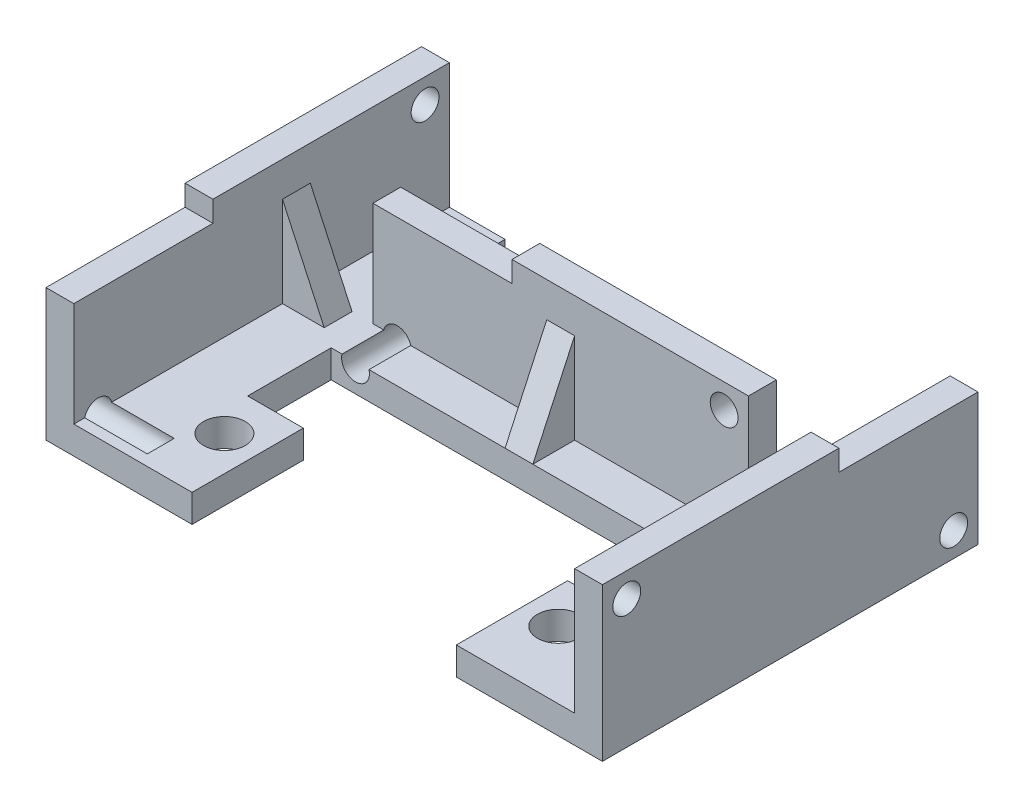
SolidWorks part; units mm, degrees
ref_plane "Front Plane" through (0, 0, 0) normal (0, 0, 1) x (1, 0, 0)
ref_plane "Top Plane" through (0, 0, 0) normal (0, 1, 0) x (1, 0, 0)
ref_plane "Right Plane" through (0, 0, 0) normal (1, 0, 0) x (0, 0, -1)
sketch "Sketch1" plane through (0, 0, 0) normal (0, 1, 0) x (1, 0, 0)
  line L0 (-13.5, 0) -> (13.5, 0)
  line L1 (13.5, 0) -> (13.5, 8)
  line L2 (13.5, 8) -> (20, 8)
  line L3 (20, 8) -> (20, -19)
  line L4 (20, -19) -> (13.5, -19)
  line L5 (13.5, -19) -> (13.5, -5)
  line L6 (13.5, -5) -> (-13.5, -5)
  line L7 (0, 0) -> (0, -5) construction
  line L8 (-13.5, -19) -> (-13.5, -5)
  line L9 (-20, -19) -> (-13.5, -19)
  line L10 (-20, 8) -> (-20, -19)
  line L11 (-13.5, 8) -> (-20, 8)
  line L12 (-13.5, 0) -> (-13.5, 8)
  dimension "D1" = 6.5
  dimension "D2" = 13.5
  dimension "D3" = 8
  dimension "D4" = 27
  dimension "D5" = 5
extrude "Boss-Extrude1" add sketch "Sketch1" along normal blind 11
sketch "Sketch2" plane through (0, 11, 0) normal (0, 1, 0) x (1, 0, 0)
  line L0 (-18, 8) -> (-18, -19)
  line L1 (-13.5, 8) -> (-20, 8) construction
  line L2 (-20, -19) -> (-13.5, -19) construction
  line L3 (-18, -19) -> (-13.5, -19)
  line L4 (-13.5, -19) -> (-13.5, -5)
  line L5 (-13.5, -5) -> (13.5, -5)
  line L6 (13.5, -5) -> (13.5, -19)
  line L7 (13.5, -19) -> (18, -19)
  line L8 (13.5, -19) -> (20, -19) construction
  line L9 (18, -19) -> (18, 8)
  line L10 (20, 8) -> (13.5, 8) construction
  line L11 (18, 8) -> (13.5, 8)
  line L12 (13.5, 8) -> (13.5, -2)
  line L13 (13.5, -2) -> (-13.5, -2)
  line L14 (-13.5, -2) -> (-13.5, 8)
  line L15 (-13.5, 8) -> (-18, 8)
  line L16 (-20, 8) -> (-20, -19) construction
  line L17 (20, -19) -> (20, 8) construction
  line L18 (13.5, 0) -> (-13.5, 0) construction
  dimension "D1" = 2
  dimension "D2" = 2
  dimension "D3" = 2
  dimension "D4" = 6.5
extrude "Cut-Extrude1" cut sketch "Sketch2" against normal blind 9
sketch "Sketch3" plane through (0, 0, 2) normal (0, 0, 1) x (1, 0, 0)
  line L0 (-13.5, 11) -> (-13.5, 9.5)
  line L1 (-13.5, 2) -> (-13.5, 11) construction
  line L2 (-13.5, 9.5) -> (-3.5, 9.5)
  line L3 (-3.5, 9.5) -> (-3.5, 11)
  line L4 (13.5, 11) -> (-13.5, 11) construction
  line L5 (-3.5, 11) -> (-13.5, 11)
  dimension "D1" = 1.5
  dimension "D2" = 10
extrude "Cut-Extrude2" cut sketch "Sketch3" against normal blind 9
sketch "Sketch4" plane through (18, 0, 0) normal (-1, 0, 0) x (0, 0, 1)
  line L0 (-8, 11) -> (-8, 9.5)
  line L1 (-8, 11) -> (-8, 0) construction
  line L2 (-8, 9.5) -> (2, 9.5)
  line L3 (2, 9.5) -> (2, 11)
  line L4 (-8, 11) -> (19, 11) construction
  line L5 (2, 11) -> (-8, 11)
  dimension "D1" = 10
  dimension "D2" = 1.5
extrude "Cut-Extrude3" cut sketch "Sketch4" against normal blind 9
sketch "Sketch5" plane through (-18, 0, 0) normal (1, 0, 0) x (0, 0, -1)
  line L0 (-19, 11) -> (-19, 9.5)
  line L1 (-19, 2) -> (-19, 11) construction
  line L2 (-19, 9.5) -> (-9, 9.5)
  line L3 (-9, 9.5) -> (-9, 11)
  line L4 (8, 11) -> (-19, 11) construction
  line L5 (-9, 11) -> (-19, 11)
  dimension "D1" = 10
  dimension "D2" = 1.5
extrude "Cut-Extrude4" cut sketch "Sketch5" against normal blind 9
sketch "Sketch6" plane through (0, 0, 0) normal (0, 0, -1) x (-1, 0, 0)
  circle A0 centre (11.75, 1.75) radius 1
  circle A1 centre (-11.75, 9.25) radius 1
extrude "Cut-Extrude5" cut sketch "Sketch6" against normal blind 9
sketch "Sketch7" plane through (20, 0, 0) normal (1, 0, 0) x (0, 0, -1)
  circle A0 centre (6.25, 1.75) radius 1
  circle A1 centre (-17.25, 9.25) radius 1
extrude "Cut-Extrude6" cut sketch "Sketch7" against normal blind 9
sketch "Sketch8" plane through (-20, 0, 0) normal (-1, 0, 0) x (0, 0, 1)
  circle A0 centre (17.25, 1.75) radius 1
  circle A1 centre (-6.25, 9.25) radius 1
extrude "Cut-Extrude10" cut sketch "Sketch8" against normal blind 9
sketch "Sketch10" plane through (0, 0, 0) normal (1, 0, 0) x (0, 0, -1)
  line L0 (-5, 2) -> (-2, 2)
  line L1 (-2, 2) -> (-2, 11) construction
  line L2 (-2, 2) -> (-2, 8.5)
  line L3 (-2, 8.5) -> (-5, 2)
  dimension "D1" = 3
  dimension "D2" = 6.5
extrude "Boss-Extrude2" add sketch "Sketch10" along normal mid plane 2
sketch "Sketch11" plane through (0, 2, 0) normal (0, 1, 0) x (1, 0, 0)
  line L0 (0, 8.5762) -> (0, 0) construction
  line L1 (-13.5, 8) -> (-14, 8)
  line L2 (-13.5, 8) -> (-18, 8) construction
  line L3 (-14, 8) -> (-14, 0)
  line L4 (-14, 0) -> (-13.5, 0)
  line L5 (-13.5, 0) -> (-13.5, 8)
  line L6 (13.5, 0) -> (13.5, 8)
  line L7 (14, 0) -> (13.5, 0)
  line L8 (14, 8) -> (14, 0)
  line L9 (13.5, 8) -> (14, 8)
  dimension "D1" = 0.5
extrude "Cut-Extrude12" cut sketch "Sketch11" against normal through all
sketch "Sketch12" plane through (0, 0, 2) normal (0, 0, 1) x (1, 0, 0)
  line L0 (-18, 8.5) -> (-15, 2)
  line L1 (-18, 2) -> (-18, 9.5) construction
  line L2 (-18, 2) -> (-13.5, 2) construction
  line L3 (-15, 2) -> (-18, 2)
  line L4 (-18, 2) -> (-18, 8.5)
  line L5 (0, 11) -> (0, 0) construction
  line L6 (13.5, 11) -> (-3.5, 11) construction
  line L7 (18, 2) -> (18, 8.5)
  line L8 (15, 2) -> (18, 2)
  line L9 (18, 8.5) -> (15, 2)
  dimension "D1" = 3
  dimension "D2" = 6.5
extrude "Boss-Extrude3" add sketch "Sketch12" along normal blind 2
sketch "Sketch13" plane through (0, 2, 0) normal (0, 1, 0) x (1, 0, 0)
  line L0 (13.5, -11) -> (9.5, -11)
  line L1 (13.5, -5) -> (13.5, -19) construction
  line L2 (9.5, -11) -> (9.5, -19)
  line L3 (9.5, -19) -> (13.5, -19)
  line L4 (0, 0) -> (0, -19) construction
  line L5 (13.5, -11) -> (13.5, -19)
  line L6 (-13.5, -11) -> (-13.5, -19)
  line L7 (-9.5, -19) -> (-13.5, -19)
  line L8 (-9.5, -11) -> (-9.5, -19)
  line L9 (-13.5, -11) -> (-9.5, -11)
  dimension "D1" = 8
  dimension "D2" = 4
extrude "Boss-Extrude4" add sketch "Sketch13" against normal blind 2
sketch "Sketch14" plane through (0, 0, 0) normal (0, -1, 0) x (-1, 0, 0)
  line L0 (0, 0) -> (0, -19.217) construction
  line L1 (-9.5, -19) -> (-20, -19) construction
  line L2 (-20, -19) -> (-20, 8) construction
  circle A0 centre (-12, -14.1745) radius 1.5
  circle A1 centre (12, -14.1745) radius 1.5
  dimension "D1" = 3
  dimension "D2" = 4.8255
  dimension "D3" = 8
extrude "Cut-Extrude13" cut sketch "Sketch14" against normal blind 10
